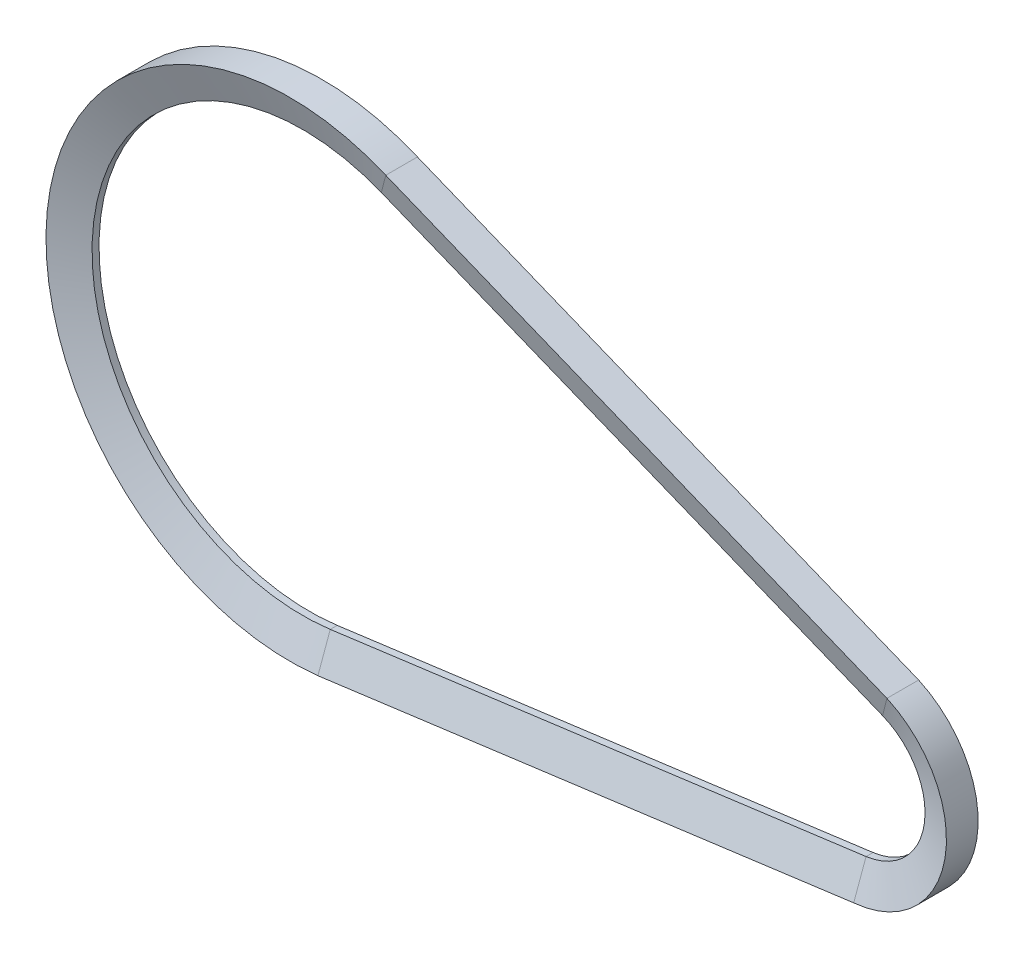
SolidWorks part; units mm, degrees
ref_plane "Front Plane" through (0, 0, 0) normal (0, 0, 1) x (1, 0, 0)
ref_plane "Top Plane" through (0, 0, 0) normal (0, 1, 0) x (1, 0, 0)
ref_plane "Right Plane" through (0, 0, 0) normal (1, 0, 0) x (0, 0, -1)
sketch "Sketch1" plane through (0, 0, 0) normal (0, 0, 1) x (1, 0, 0)
  line L0 (6.1247, -46.0949) -> (124.4757, -30.3693)
  line L1 (17.4127, 43.1167) -> (128.117, -1.5914)
  arc A0 (17.4127, 43.1167) -> (6.1247, -46.0949) centre (0, 0) ccw
  arc A1 (124.4757, -30.3693) -> (128.117, -1.5914) centre (122.5, -15.5) ccw
  dimension "D1" = 15.5
  dimension "D3" = 93
  dimension "D4" = 30
  dimension "D2" = 122.5
ref_plane "Plane1" through (6.1247, 0, 0) normal (1, 0, 0) x (0, 0, -1)
sketch "Sketch2" plane through (6.1247, 0, 0) normal (1, 0, 0) x (0, 0, -1)
  line L0 (0, -46.0949) -> (0, -12.0629) construction
  line L1 (-0.7702, -46.0949) -> (0.7702, -46.0949)
  line L2 (-3.5, -53.5949) -> (3.5, -53.5949)
  line L3 (-0.7702, -46.0949) -> (-3.5, -53.5949)
  line L4 (0.7702, -46.0949) -> (3.5, -53.5949)
  line L5 (0, -46.0949) -> (0, -53.5949) construction
  dimension "D1" = 7
  dimension "D2" = 7.5
  dimension "D3" = 40
sweep "Sweep1" add profiles "Sketch2" path "Sketch1"
